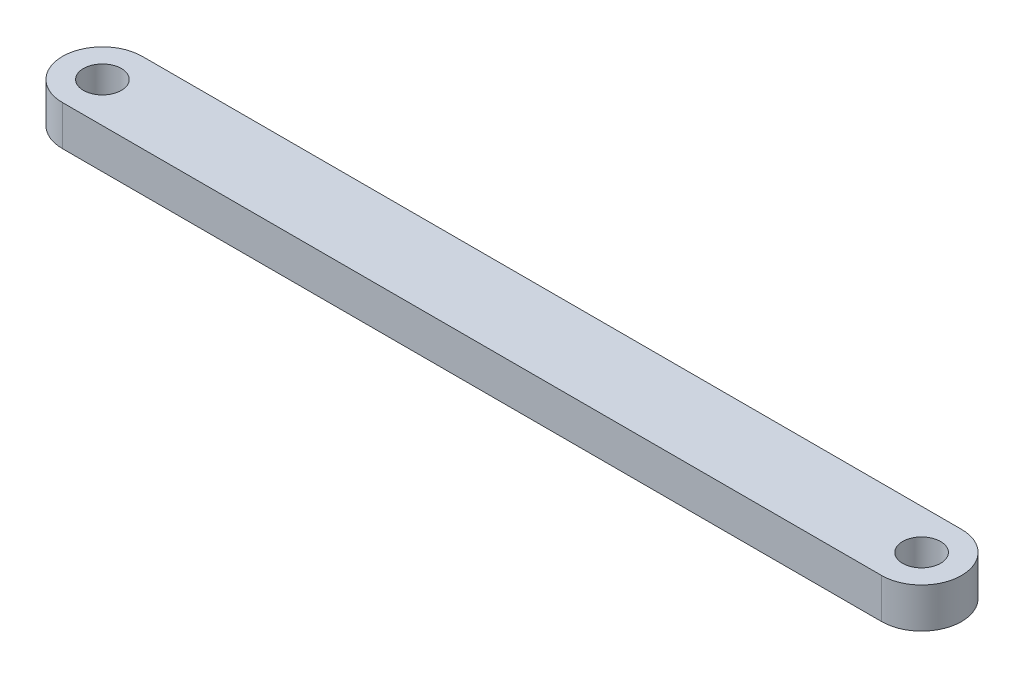
SolidWorks part; units mm, degrees
ref_plane "Front Plane" through (0, 0, 0) normal (0, 0, 1) x (1, 0, 0)
ref_plane "Top Plane" through (0, 0, 0) normal (0, 1, 0) x (1, 0, 0)
ref_plane "Right Plane" through (0, 0, 0) normal (1, 0, 0) x (0, 0, -1)
sketch "Sketch1" plane through (0, 0, 0) normal (0, 1, 0) x (1, 0, 0)
  line L0 (-20.5, 0) -> (20.5, 0) construction
  line L1 (-20.5, 2) -> (20.5, 2)
  line L2 (-20.5, -2) -> (20.5, -2)
  arc A0 (-20.5, 2) -> (-20.5, -2) centre (-20.5, 0) ccw
  arc A1 (20.5, -2) -> (20.5, 2) centre (20.5, 0) ccw
  circle A2 centre (-20.5, 0) radius 0.95
  circle A3 centre (20.5, 0) radius 0.95
  point P2 (0, 0)
  dimension "D2" = 2
  dimension "D3" = 1.9
  dimension "D4" = 1.9
  dimension "D1" = 41
extrude "Boss-Extrude1" add sketch "Sketch1" along normal mid plane 2
